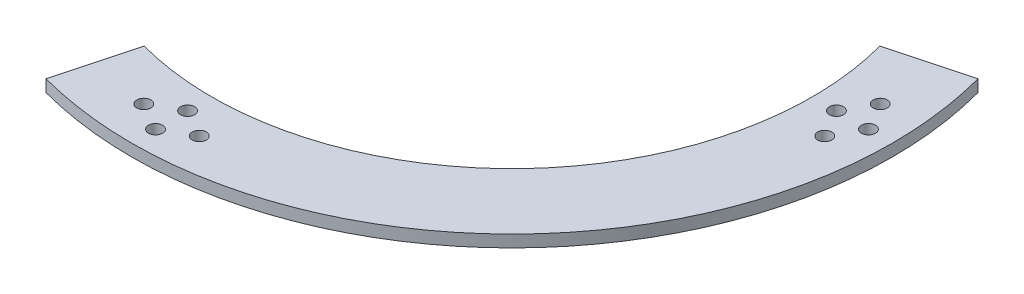
SolidWorks part; units mm, degrees
ref_plane "前视基准面" through (0, 0, 0) normal (0, 0, 1) x (1, 0, 0)
ref_plane "上视基准面" through (0, 0, 0) normal (0, 1, 0) x (1, 0, 0)
ref_plane "右视基准面" through (0, 0, 0) normal (1, 0, 0) x (0, 0, -1)
other "Configuration Table"
sketch "草图1" plane through (0, 0, 0) normal (0, 1, 0) x (1, 0, 0)
  line L0 (-19.4114, -72.4444) -> (-24.5878, -91.763)
  line L1 (72.4444, 19.4114) -> (91.763, 24.5878)
  line L2 (0, 0) -> (-19.4114, -72.4444) construction
  line L3 (0, 0) -> (72.4444, 19.4114) construction
  line L4 (0, 0) -> (0, -95) construction
  line L5 (0, 0) -> (95, 0) construction
  line L6 (0, 0) -> (0, -81) construction
  line L7 (0, 0) -> (81, 0) construction
  arc A0 (-24.5878, -91.763) -> (91.763, 24.5878) centre (0, 0) ccw
  arc A1 (-19.4114, -72.4444) -> (72.4444, 19.4114) centre (0, 0) ccw
  circle A2 centre (0, -89) radius 1.75
  circle A3 centre (0, -81) radius 1.75
  circle A4 centre (-6.9282, -85) radius 1.75
  circle A5 centre (6.9282, -85) radius 1.75
  circle A6 centre (85, -6.9282) radius 1.75
  circle A7 centre (81, 0) radius 1.75
  circle A8 centre (85, 6.9282) radius 1.75
  circle A9 centre (89, 0) radius 1.75
  dimension "D1" = 95
  dimension "D2" = 75
  dimension "D6" = 3.5
  dimension "D3" = 120
  dimension "D4" = 90
  dimension "D5" = 15
  dimension "D7" = 89
  dimension "D8" = 8
  dimension "D9" = 8
  dimension "D10" = 8
  dimension "D11" = 8
  dimension "D12" = 8
  dimension "D14" = 90
  dimension "D13" = 2
extrude "凸台-拉伸1" add sketch "草图1" along normal blind 3
